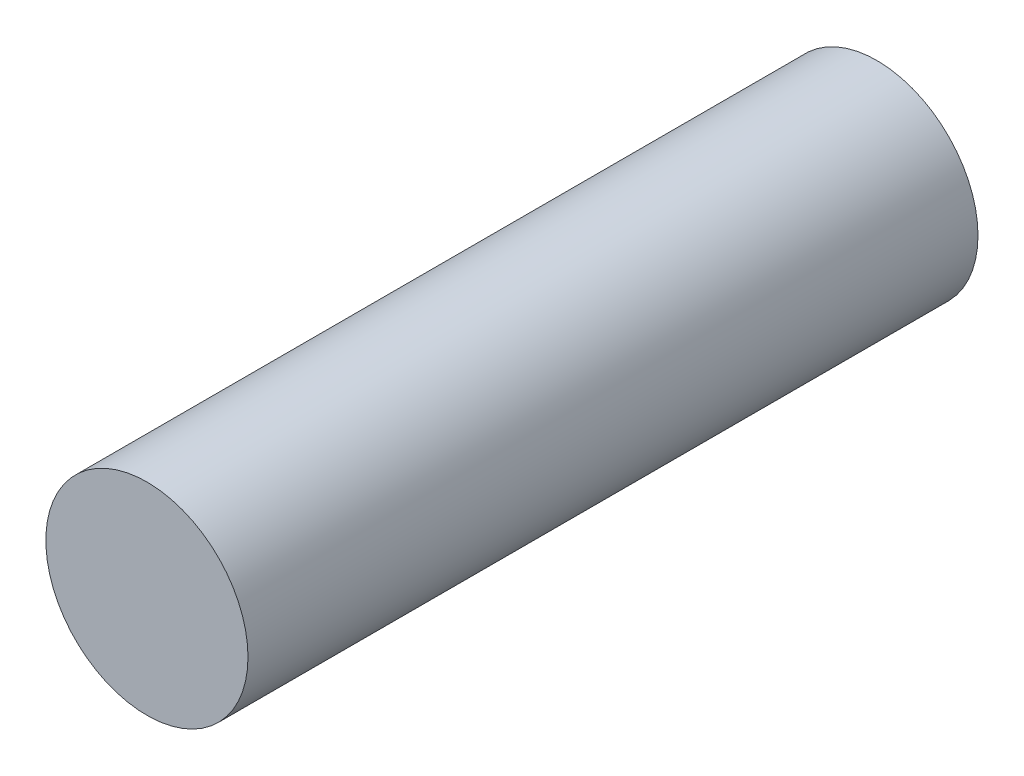
SolidWorks part; units mm, degrees
ref_plane "Plan de face" through (0, 0, 0) normal (0, 0, 1) x (1, 0, 0)
ref_plane "Plan de dessus" through (0, 0, 0) normal (0, 1, 0) x (1, 0, 0)
ref_plane "Plan de droite" through (0, 0, 0) normal (1, 0, 0) x (0, 0, -1)
sketch "Esquisse1" plane through (0, 0, 0) normal (0, 0, 1) x (1, 0, 0)
  circle A0 centre (0, 0) radius 9
  dimension "D1" = 18
extrude "Boss.-Extru.1" add sketch "Esquisse1" along normal blind 65
